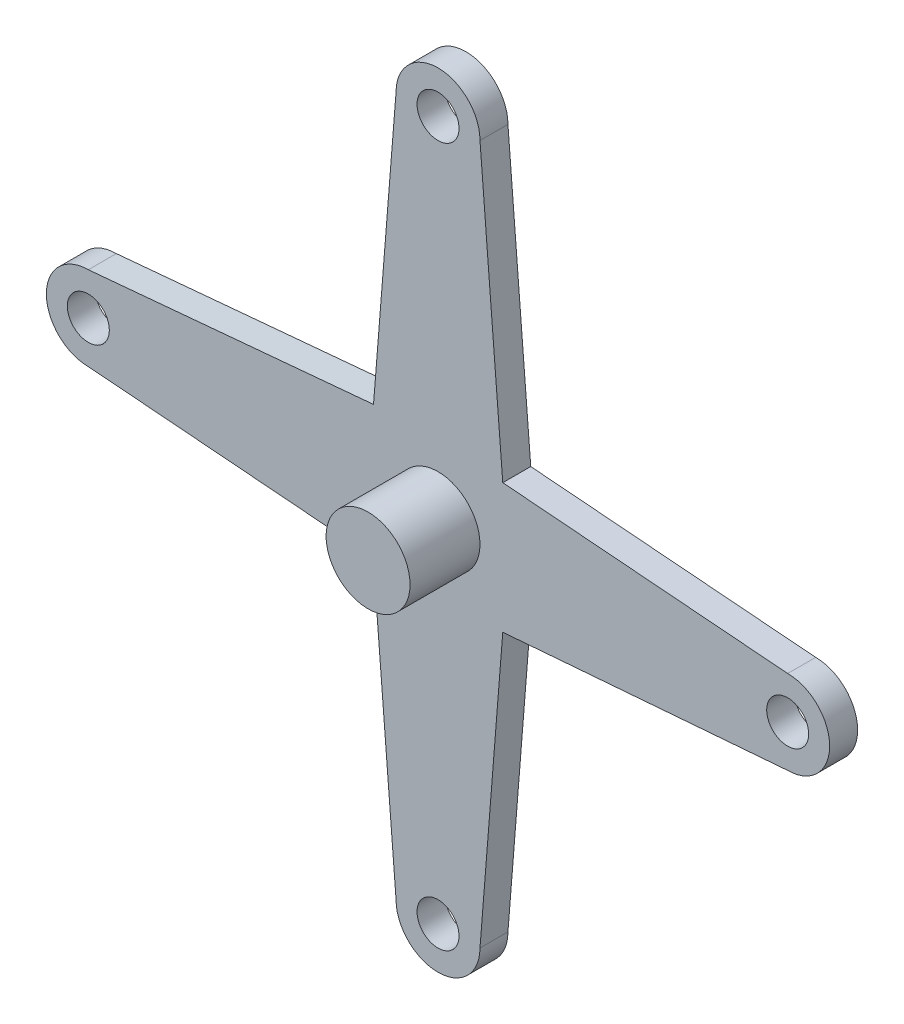
SolidWorks part; units mm, degrees
ref_plane "Front Plane" through (0, 0, 0) normal (0, 0, 1) x (1, 0, 0)
ref_plane "Top Plane" through (0, 0, 0) normal (0, 1, 0) x (1, 0, 0)
ref_plane "Right Plane" through (0, 0, 0) normal (1, 0, 0) x (0, 0, -1)
sketch "Sketch1" plane through (0, 0, 0) normal (0, 0, 1) x (1, 0, 0)
  line L1 (4.6296, 4.6296) -> (25, 3)
  line L4 (4.6296, -4.6296) -> (3, -25)
  line L8 (-4.6115, 4.8557) -> (-3, 25)
  line L9 (-4.6115, 4.8557) -> (-25, 3)
  line L10 (4.6296, 4.6296) -> (3, 25)
  line L11 (4.6296, -4.6296) -> (25, -3)
  line L12 (-4.6296, -4.6296) -> (-3, -25)
  line L13 (-4.6296, -4.6296) -> (-25, -3)
  line L14 (0, -5) -> (0.7949, -4.9364) [skipped]
  line L15 (0, -5) -> (-0.7949, -4.9364) [skipped]
  line L16 (5, 0) -> (4.9364, 0.7949) [skipped]
  line L17 (-5, 0) -> (-4.9364, 0.7949) [skipped]
  line L18 (-5, 0) -> (-4.9364, -0.7949) [skipped]
  line L19 (0, 5) -> (-0.7949, 4.9364) [skipped]
  circle A1 centre (0, 25) radius 1.5
  arc A2 (3, 25) -> (-3, 25) centre (0, 25) ccw
  arc A3 (25, -3) -> (25, 3) centre (25, 0) ccw
  circle A4 centre (25, 0) radius 1.5
  arc A5 (-3, -25) -> (3, -25) centre (0, -25) ccw
  circle A6 centre (0, -25) radius 1.5
  arc A7 (-25, 3) -> (-25, -3) centre (-25, 0) ccw
  circle A8 centre (-25, 0) radius 1.5
  dimension "D3" = 4
extrude "Boss-Extrude1" add sketch "Sketch1" along normal blind 2
sketch "Sketch2" plane through (0, 0, 2) normal (0, 0, 1) x (1, 0, 0)
  circle A0 centre (0, 0) radius 3
extrude "Boss-Extrude2" add sketch "Sketch2" along normal blind 5
